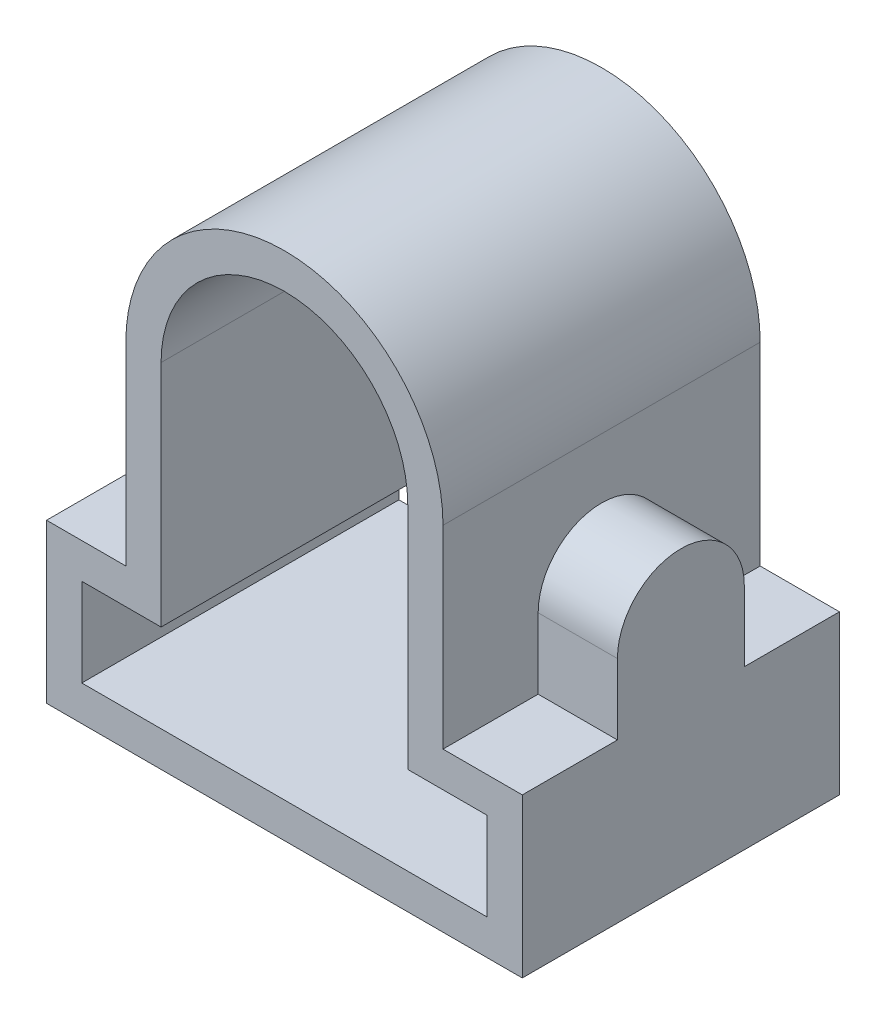
SolidWorks part; units mm, degrees
ref_plane "Front Plane" through (0, 0, 0) normal (0, 0, 1) x (1, 0, 0)
ref_plane "Top Plane" through (0, 0, 0) normal (0, 1, 0) x (1, 0, 0)
ref_plane "Right Plane" through (0, 0, 0) normal (1, 0, 0) x (0, 0, -1)
sketch "Sketch1" plane through (0, 0, 0) normal (0, 0, 1) x (1, 0, 0)
  line L0 (-67.5, 0) -> (67.5, 0)
  line L2 (55, 0) -> (-55, 0) construction
  line L3 (67.5, 0) -> (67.5, 45)
  line L4 (67.5, 45) -> (45, 45)
  line L5 (45, 45) -> (45, 100)
  line L6 (0, -55) -> (0, 55) construction
  line L7 (-67.5, 0) -> (-67.5, 45)
  line L8 (-67.5, 45) -> (-45, 45)
  line L9 (-45, 45) -> (-45, 100)
  line L10 (-35, 35) -> (-35, 100)
  line L11 (-57.5, 35) -> (-35, 35)
  line L12 (-57.5, 10) -> (-57.5, 35)
  line L13 (-57.5, 10) -> (57.5, 10)
  line L14 (57.5, 10) -> (57.5, 35)
  line L15 (57.5, 35) -> (35, 35)
  line L16 (35, 35) -> (35, 100)
  arc A0 (45, 100) -> (-45, 100) centre (0, 100) ccw
  arc A1 (35, 100) -> (-35, 100) centre (0, 100) ccw
  point P4 (0, 0)
  dimension "D1" = 45
  dimension "D2" = 135
  dimension "D3" = 45
  dimension "D4" = 100
  dimension "D5" = 10
extrude "Boss-Extrude1" add sketch "Sketch1" along normal mid plane 90
sketch "Sketch2" plane through (45, 0, 0) normal (1, 0, 0) x (0, 0, -1)
  line L0 (-18, 45) -> (-18, 65)
  line L1 (-45, 45) -> (45, 45) construction
  line L2 (18, 65) -> (18, 45)
  line L3 (-45, 45) -> (45, 45) construction
  line L4 (0, 74.25) -> (0, -74.25) construction
  line L5 (-18, 45) -> (18, 45)
  line L6 (49.5, 0) -> (-49.5, 0) construction
  arc A0 (-18, 65) -> (18, 65) centre (0, 65) cw
  dimension "D1" = 18
  dimension "D2" = 65
extrude "Boss-Extrude2" add sketch "Sketch2" along normal up to surface (22.5 mm away) up to face at (67.5, 22.5, 0)
